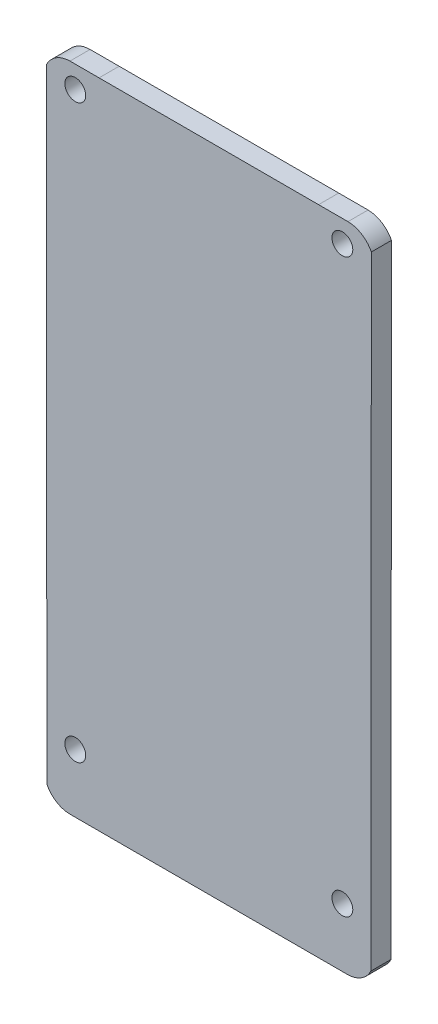
SolidWorks part; units mm, degrees
ref_plane "Front Plane" through (0, 0, 0) normal (0, 0, 1) x (1, 0, 0)
ref_plane "Top Plane" through (0, 0, 0) normal (0, 1, 0) x (1, 0, 0)
ref_plane "Right Plane" through (0, 0, 0) normal (1, 0, 0) x (0, 0, -1)
sketch "Sketch1" plane through (0, 0, 0) normal (0, 0, 1) x (-1, 0, 0)
  line L9 (19.0264, 44.5651) -> (15, 44.5669)
  line L10 (17, 42.5734) -> (22.1394, 42.5734) construction
  line L11 (-15, 44.5732) -> (-19.0264, 44.5732)
  line L12 (-22.1448, 42.5734) -> (-17, 42.5734) construction
  line L13 (-19.0124, -44.5658) -> (-15, -44.5674)
  line L14 (-17, -42.5734) -> (-22.2126, -42.5734) construction
  line L15 (15, -44.5734) -> (15, -44.5737)
  line L16 (15, -44.5737) -> (18.9755, -44.5738)
  line L17 (22.1813, -42.5734) -> (17, -42.5734) construction
  line L18 (22.1394, 42.5734) -> (22.1813, -42.5734)
  line L19 (-22.2126, -42.5734) -> (-22.1448, 42.5734)
  line L20 (-15, 44.5732) -> (15, 44.5669)
  line L21 (15, -44.5737) -> (-15, -44.5674)
  arc A8 (22.1394, 42.5734) -> (19.0264, 44.5651) centre (18.9484, 41.0147) ccw
  arc A9 (15, 44.5669) -> (17, 42.5734) centre (17, 44.5734) ccw construction
  arc A10 (-17, 42.5734) -> (-15, 44.5732) centre (-17, 44.5734) ccw construction
  arc A11 (-19.0264, 44.5732) -> (-22.1448, 42.5734) centre (-18.9499, 41.0227) ccw
  arc A12 (-22.2126, -42.5734) -> (-19.0124, -44.5658) centre (-18.9746, -40.9388) ccw
  arc A13 (-15, -44.5674) -> (-17, -42.5734) centre (-17, -44.5734) ccw construction
  arc A14 (17, -42.5734) -> (15, -44.5734) centre (17, -44.5734) ccw construction
  arc A15 (18.9755, -44.5738) -> (22.1813, -42.5734) centre (18.9392, -40.9468) ccw
extrude "Boss-Extrude1" add sketch "Sketch1" along normal blind 2.75
sketch "Sketch2" plane through (0, 0, 2.75) normal (0, 0, 1) x (1, 0, 0)
  line L1 (-18.25, -36.5342) -> (18.25, -36.5342) construction
  line L2 (-18.25, -36.5342) -> (-18.25, 41.5658) construction
  line L3 (-18.25, 41.5658) -> (18.25, 41.5658) construction
  line L4 (18.25, -36.5342) -> (18.25, 41.5658) construction
  line L5 (-18.25, -36.5342) -> (18.25, 41.5658) construction
  line L6 (-18.25, 41.5658) -> (18.25, -36.5342) construction
  circle A0 centre (-18.25, 41.5658) radius 1.425
  circle A1 centre (18.25, 41.5658) radius 1.425
  circle A2 centre (18.25, -36.5342) radius 1.425
  circle A3 centre (-18.25, -36.5342) radius 1.425
  point P0 (0, 2.5158)
  dimension "D3" = 2.85
  dimension "D1" = 36.5
  dimension "D2" = 78.1
  dimension "D4" = 3
extrude "Cut-Extrude1" cut sketch "Sketch2" against normal through all both and the other way through all
